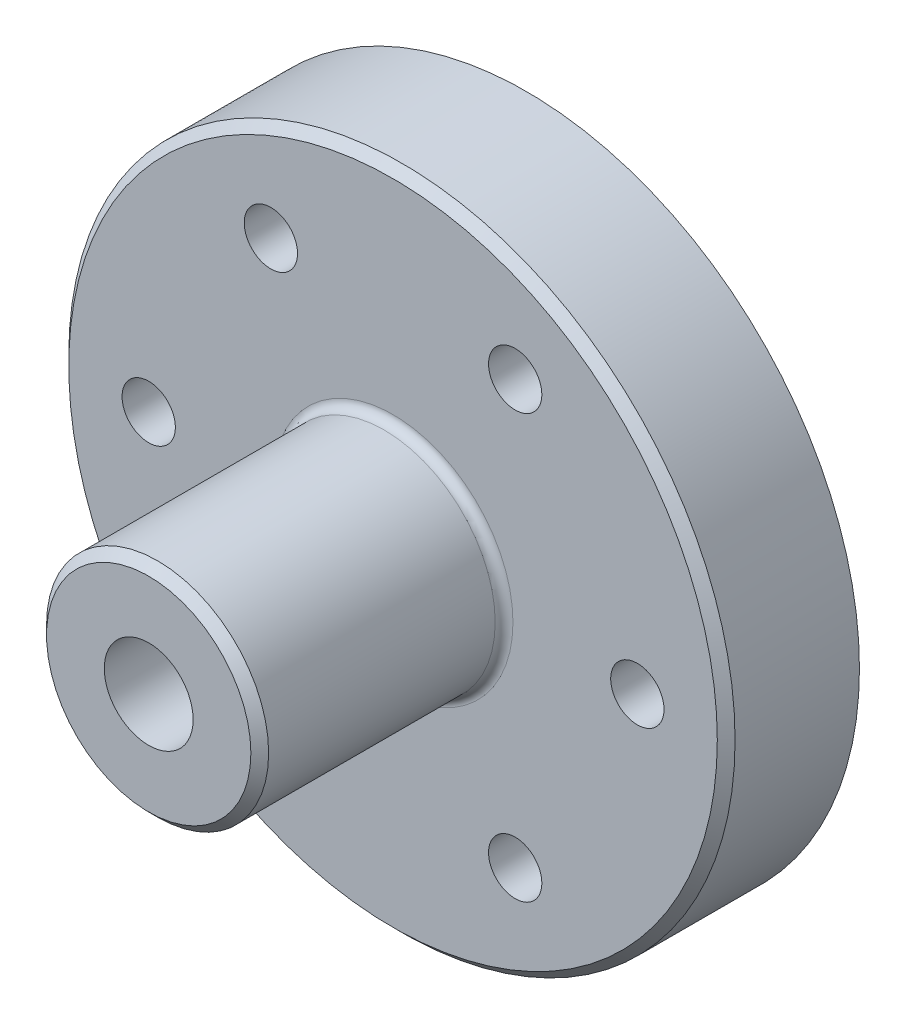
SolidWorks part; units mm, degrees
ref_plane "前视基准面" through (0, 0, 0) normal (0, 0, 1) x (1, 0, 0)
ref_plane "上视基准面" through (0, 0, 0) normal (0, 1, 0) x (1, 0, 0)
ref_plane "右视基准面" through (0, 0, 0) normal (1, 0, 0) x (0, 0, -1)
other "Configuration Table"
sketch "草图1" plane through (0, 0, 0) normal (0, 0, 1) x (1, 0, 0)
  circle A0 centre (0, 0) radius 75
  circle A1 centre (-55, 0) radius 6
  circle A2 centre (-27.5, 47.6314) radius 6
  circle A3 centre (27.5, 47.6314) radius 6
  circle A4 centre (55, 0) radius 6
  circle A5 centre (27.5, -47.6314) radius 6
  circle A6 centre (-27.5, -47.6314) radius 6
  point P18 (0, 0)
  dimension "D1" = 150
  dimension "D2" = 12
  dimension "D3" = 55
  dimension "D4" = 6
extrude "凸台-拉伸1" add sketch "草图1" along normal blind 30
sketch "草图2" plane through (0, 0, 30) normal (0, 0, 1) x (1, 0, 0)
  circle A0 centre (0, 0) radius 25
  circle A1 centre (0, 0) radius 10
  dimension "D1" = 50
  dimension "D2" = 20
extrude "凸台-拉伸2" add sketch "草图2" along normal blind 55
chamfer "倒角1" distance 2 angle 45 2 edges at (75, 0, 30) (25, 0, 85)
fillet "圆角1" radius 2 1 edges at (25, 0, 30)
